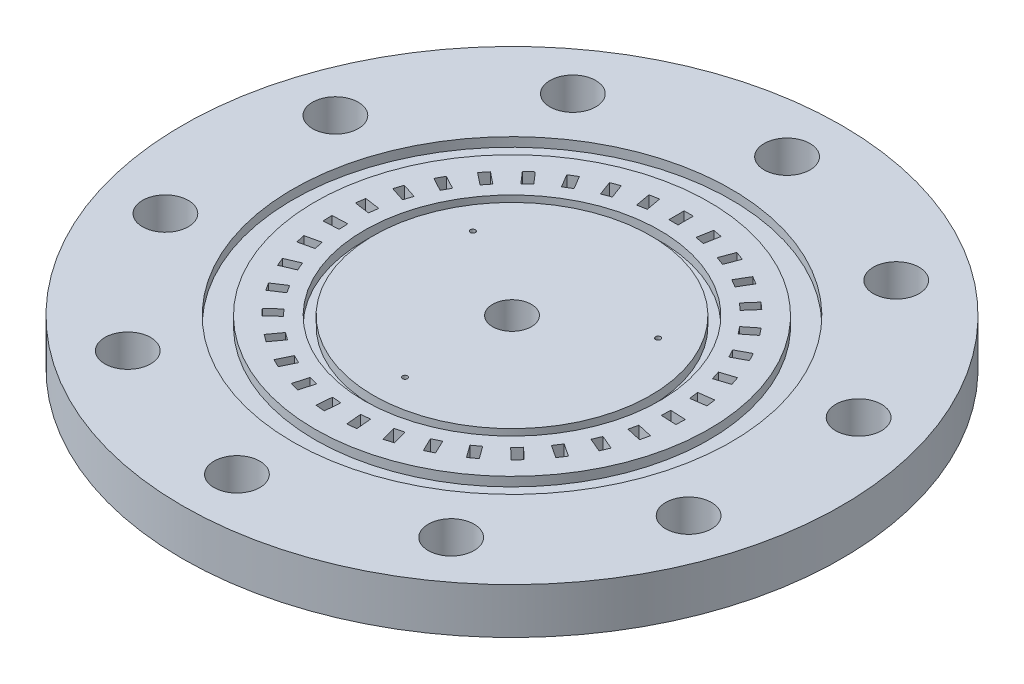
SolidWorks part; units mm, degrees
ref_plane "Front Plane" through (0, 0, 0) normal (0, 0, 1) x (1, 0, 0)
ref_plane "Top Plane" through (0, 0, 0) normal (0, 1, 0) x (1, 0, 0)
ref_plane "Right Plane" through (0, 0, 0) normal (1, 0, 0) x (0, 0, -1)
sketch "Sketch1" plane through (0, 0, 0) normal (0, 1, 0) x (1, 0, 0)
  circle A0 centre (0, 0) radius 107.8268
  circle A3 centre (0, 90) radius 7.5
  circle A4 centre (52.9007, 72.8115) radius 7.5
  circle A5 centre (85.5951, 27.8115) radius 7.5
  circle A6 centre (85.5951, -27.8115) radius 7.5
  circle A7 centre (52.9007, -72.8115) radius 7.5
  circle A8 centre (0, -90) radius 7.5
  circle A9 centre (-52.9007, -72.8115) radius 7.5
  circle A10 centre (-85.5951, -27.8115) radius 7.5
  circle A11 centre (-85.5951, 27.8115) radius 7.5
  circle A12 centre (-52.9007, 72.8115) radius 7.5
  circle A13 centre (0, 0) radius 6.35
  point P25 (0, 0)
  dimension "D1" = 215.6537
  dimension "D2" = 15
  dimension "D5" = 12.7
  dimension "D3" = 90
  dimension "D4" = 10
extrude "Faceplate Extrusion" add sketch "Sketch1" along normal blind 15
sketch "Regen Channels" plane through (0, 15, 0) normal (0, 1, 0) x (1, 0, 0)
  line L0 (0, 47.8268) -> (20.5935, 47.8268) construction
  line L5 (-1.5, 57.8268) -> (1.5, 57.8268)
  line L182 (-1.5, 57.8268) -> (-1.5, 52.8268)
  line L183 (-1.5, 52.8268) -> (1.5, 52.8268)
  line L184 (1.5, 57.8268) -> (1.5, 52.8268)
  line L185 (0, 64.4478) -> (20.5935, 64.4478) construction
  circle A0 centre (0, 0) radius 64.4478 construction
  circle A1 centre (0, 0) radius 47.8268 construction
  point P8 (0, 52.8268)
  dimension "D1" = 128.8957
  dimension "D2" = 95.6537
  dimension "D3" = 3
  dimension "D4" = 5
  dimension "D5" = 5
extrude "Regen Channel" cut sketch "Regen Channels" against normal through all
pattern_circular "Regen Channels Revolve" count 35 over 360 about axis through (0, 0, 0) along (0, 1, 0) of "Regen Channel"
sketch "Sketch30" plane through (0, 0, 0) normal (0, -1, 0) x (1, 0, 0)
  circle A0 centre (0, 0) radius 64.4478
  circle A1 centre (0, 0) radius 71.6868
  dimension "D1" = 128.8957
  dimension "D2" = 143.3737
extrude "Interfacing O-Ring Slot 1" cut sketch "Sketch30" against normal blind 3
sketch "Sketch32" plane through (0, 15, 0) normal (0, 1, 0) x (1, 0, 0)
  circle A0 centre (0, 0) radius 64.4478
  circle A1 centre (0, 0) radius 71.687
  dimension "D1" = 128.8957
  dimension "D2" = 143.374
extrude "Interfacing O-Ring Slot 2" cut sketch "Sketch32" against normal blind 3
sketch "Sketch33" plane through (0, 15, 0) normal (0, 1, 0) x (1, 0, 0)
  line L0 (-49.7778, 17.751) -> (-50.7048, 14.8978) construction
  circle A0 centre (0, 0) radius 48.33
  circle A1 centre (0, 0) radius 45.33
  circle A2 centre (0, 0) radius 46.83 construction
  dimension "D1" = 3
  dimension "D2" = 93.66
  dimension "D3" = 1.5
extrude "Manifold O-Ring Slot 1" cut sketch "Sketch33" against normal blind 3
sketch "Sketch34" plane through (0, 0, 0) normal (0, -1, 0) x (1, 0, 0)
  circle A0 centre (0, 0) radius 48.33
  circle A1 centre (0, 0) radius 45.33
  circle A2 centre (0, 0) radius 46.83 construction
  dimension "D2" = 3
  dimension "D3" = 93.66
  dimension "D1" = 93.66
extrude "Manifold O-Ring Slot 2" cut sketch "Sketch34" against normal blind 3
sketch "Sketch35" plane through (0, 0, 0) normal (0, -1, 0) x (1, 0, 0)
  circle A0 centre (0, 0) radius 35 construction
  circle A1 centre (0, 35) radius 0.8262
  circle A2 centre (30.3109, -17.5) radius 0.8262
  circle A3 centre (-30.3109, -17.5) radius 0.8262
  point P11 (0, 0)
  dimension "D3" = 3
  dimension "D1" = 70
  dimension "D2" = 1.6524
extrude "Fuel Bypass Channels" cut sketch "Sketch35" against normal through all
equation "\"FuelDia\"= 1.6524"
equation "\"OxDia\"=1.82924"
equation "\"DistOrifice\"= 10"
equation "\"CantAngle\"= 25deg"
equation "\"RadialDistOrifice\"= 60"
equation "\"Chan_amt\"= 35"
equation "\"Chan_wid\"= 3"
equation "\"Chan_heig\"= 5"
equation "\"bolt_diam\"= 15"
equation "\"D3@Regen Channels\"=\"Chan_wid\""
equation "\"D4@Regen Channels\"=\"Chan_heig\""
equation "\"D1@Regen Channels Revolve\"=\"Chan_amt\""
equation "\"D2@Sketch1\"=\"bolt_diam\""
equation "\"oring_inner\"= 128.8956920"
equation "\"D1@Sketch32\"=\"oring_inner\""
equation "\"oring_outer\"=143.374"
equation "\"D2@Sketch32\"=\"oring_outer\""
equation "\"oring_thickness\"=3"
equation "\"D1@Interfacing O-Ring Slot 1\" = \"oring_thickness\""
equation "\"D1@Interfacing O-Ring Slot 2\" = \"oring_thickness\""
equation "\"TorchIgniter\"=12.7"
equation "\"D5@Sketch1\"=\"TorchIgniter\""
equation "\"D2@Sketch35\" = \"FuelDia\""
equation "\"D1@Sketch35\"=\"RadialDistOrifice\" + \"DistOrifice\""
equation "\"t_plate\"=15"
equation "\"D1@Faceplate Extrusion\"=\"t_plate\""
